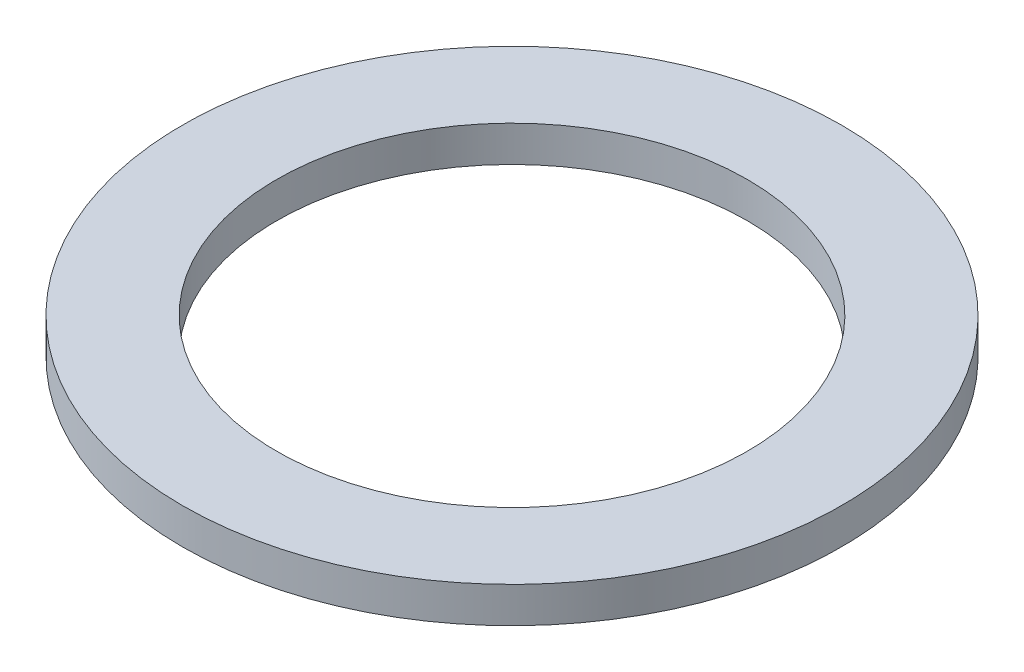
SolidWorks part; units mm, degrees
ref_plane "Front Plane" through (0, 0, 0) normal (0, 0, 1) x (1, 0, 0)
ref_plane "Top Plane" through (0, 0, 0) normal (0, 1, 0) x (1, 0, 0)
ref_plane "Right Plane" through (0, 0, 0) normal (1, 0, 0) x (0, 0, -1)
sketch "Sketch1" plane through (0, 0, 0) normal (0, 1, 0) x (1, 0, 0)
  circle A0 centre (0, 0) radius 6.35
  circle A1 centre (0, 0) radius 8.89
  dimension "D1" = 17.78
  dimension "D2" = 12.7
extrude "Boss-Extrude1" add sketch "Sketch1" along normal blind 0.9652
